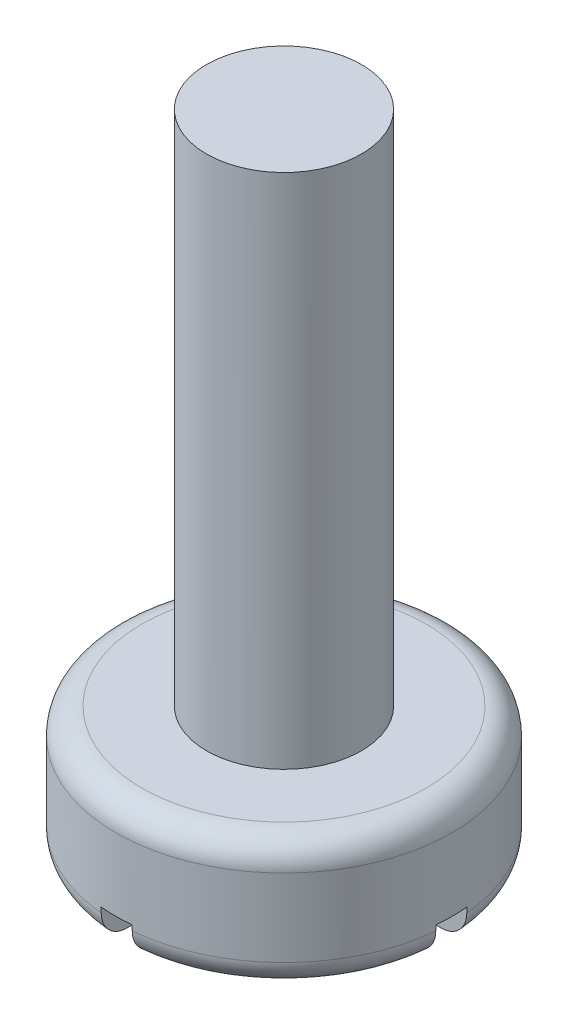
SolidWorks part; units mm, degrees
material "Plain Carbon Steel"
ref_plane "Front Plane" through (0, 0, 0) normal (0, 0, 1) x (1, 0, 0)
ref_plane "Top Plane" through (0, 0, 0) normal (0, 1, 0) x (1, 0, 0)
ref_plane "Right Plane" through (0, 0, 0) normal (1, 0, 0) x (0, 0, -1)
sketch "Sketch1" plane through (0, 0, 0) normal (0, 1, 0) x (1, 0, 0)
  circle A0 centre (0, 0) radius 3
  dimension "D1" = 6
extrude "Boss-Extrude1" add sketch "Sketch1" along normal blind 20
cosmetic thread "Cosmetic Thread1" parameters "D1"=30, "D2"=0.3
sketch "Sketch2" plane through (0, 0, 0) normal (0, 0, 1) x (1, 0, 0)
  line L0 (0, 0) -> (0, -5)
  line L1 (-5.5, 0) -> (0, 0)
  line L2 (-6.5, -1) -> (-6.5, -4)
  line L3 (-5.5, -5) -> (0, -5)
  arc A2 (-6.5, -4) -> (-5.5, -5) centre (-5.5, -4) ccw
  arc A3 (-5.5, 0) -> (-6.5, -1) centre (-5.5, -1) ccw
  point P9 (6.5, -5)
  point P12 (-6.5, -5)
  point P15 (-6.5, 0)
  dimension "D1" = 13
  dimension "D2" = 6.5
  dimension "D3" = 5
  dimension "D4" = 0
revolve "Revolve1" add sketch "Sketch2" angle 360 about L0
sketch "Sketch3" plane through (0, -5, 0) normal (0, -1, 0) x (1, 0, 0)
  line L0 (0, 8.3754) -> (0, -7.9305) construction
  line L1 (0.6, 8.3754) -> (-0.6, 8.3754)
  line L2 (0.6, 8.3754) -> (0.6, 0.8)
  line L3 (0.6, -7.9305) -> (-0.6, -7.9305)
  line L4 (-0.6, 8.3754) -> (-0.6, 0.8)
  line L5 (-7.3941, -0.6) -> (-0.8, -0.6)
  line L6 (-7.3941, -0.6) -> (-7.3941, 0.6)
  line L7 (-7.3941, 0.6) -> (-0.8, 0.6)
  line L8 (8.8402, -0.6) -> (8.8402, 0.6)
  line L9 (8.8402, 0) -> (-7.3941, 0) construction
  line L10 (0.8, 0.6) -> (8.8402, 0.6)
  line L11 (-0.6, -0.8) -> (-0.6, -7.9305)
  line L12 (0.8, -0.6) -> (8.8402, -0.6)
  line L13 (0.6, -0.8) -> (0.6, -7.9305)
  line L14 (0.6, 0.8) -> (0.8, 0.6)
  line L15 (0.8, -0.6) -> (0.6, -0.8)
  line L16 (-0.8, -0.6) -> (-0.6, -0.8)
  line L17 (-0.8, 0.6) -> (-0.6, 0.8)
  point P12 (0, 0)
  point P13 (-0.6, 0.6)
  point P16 (-0.6, -0.6)
  point P17 (0.6, 0.6)
  point P18 (0.6, -0.6)
  dimension "D1" = 1.2
  dimension "D2" = 1.2
extrude "Cut-Extrude1" cut sketch "Sketch3" against normal blind 1.2
